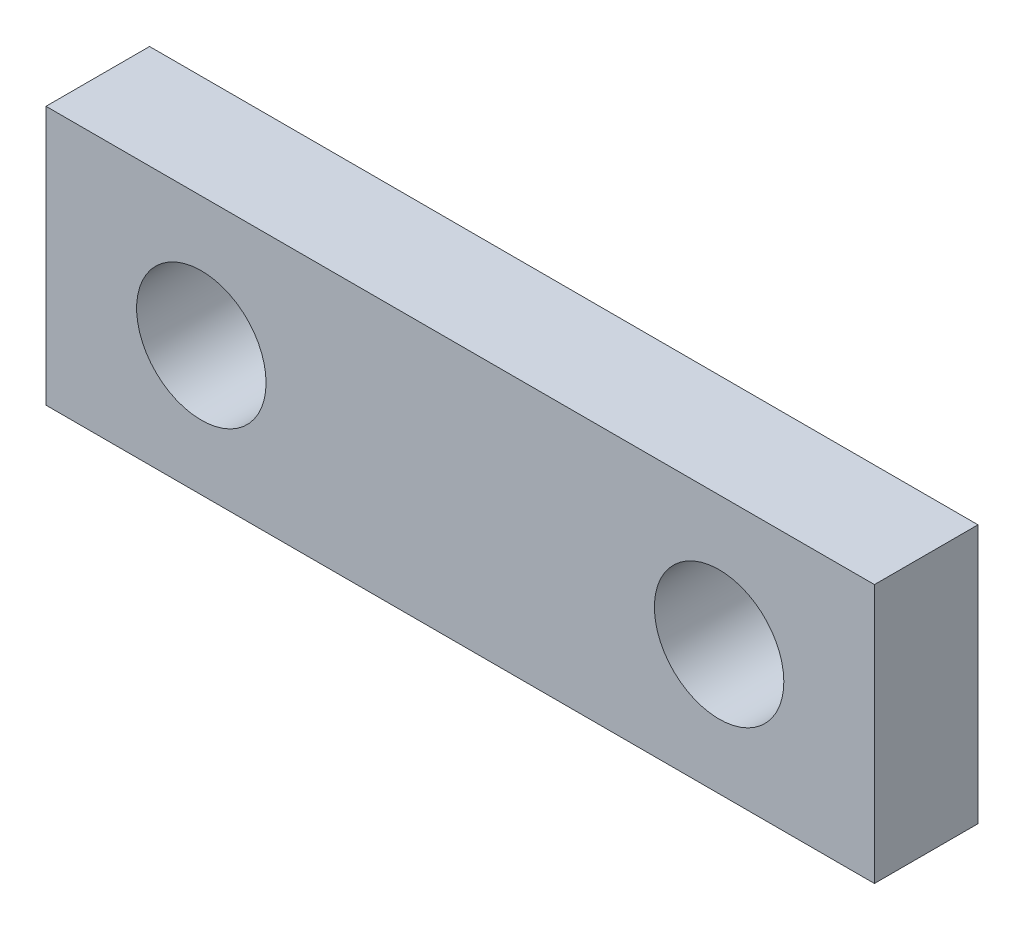
SolidWorks part; units mm, degrees
ref_plane "Ebene vorne" through (0, 0, 0) normal (0, 0, 1) x (1, 0, 0)
ref_plane "Ebene oben" through (0, 0, 0) normal (0, 1, 0) x (1, 0, 0)
ref_plane "Ebene rechts" through (0, 0, 0) normal (1, 0, 0) x (0, 0, -1)
sketch "Skizze1" plane through (0, 0, 0) normal (0, 0, 1) x (1, 0, 0)
  line L1 (0, 0) -> (16, 0)
  line L2 (0, 0) -> (0, 5)
  line L3 (0, 5) -> (16, 5)
  line L4 (16, 0) -> (16, 5)
  dimension "D1" = 16
  dimension "D2" = 5
extrude "Aufsatz-Linear austragen1" add sketch "Skizze1" along normal blind 2
hole_wizard "M3 Gewindebohrung1" positions "Skizze2" profile "Skizze3" tap size "M3" standard "DIN" end condition up to next
sketch "Skizze2" plane through (0, 0, 2) normal (0, 0, 1) x (1, 0, 0)
  line L0 (0, 5) -> (0, 0) construction
  line L1 (16, 0) -> (16, 5) construction
  line L2 (0, 0) -> (16, 0) construction
  point P0 (3, 2.5)
  point P2 (13, 2.5)
  dimension "D1" = 3
  dimension "D2" = 3
  dimension "D3" = 2.5
  dimension "D4" = 2.5
sketch "Skizze3" plane through (3, 2.5, 2) normal (1, 0, 0) x (0, -1, 0)
  line L0 (0, 0) -> (0, 2)
  line L1 (0, 2) -> (1.25, 2)
  line L2 (1.25, 2) -> (1.25, 0)
  line L5 (1.25, 0) -> (0, 0)
  line L11 (0, -6.35) -> (0, 107.95) construction
  dimension "Bohrerdurchmesser" = 2.5
  dimension "Bohrungstiefe" = 2
cosmetic thread "Bohrungsgewinde1"
cosmetic thread "Bohrungsgewinde2"
